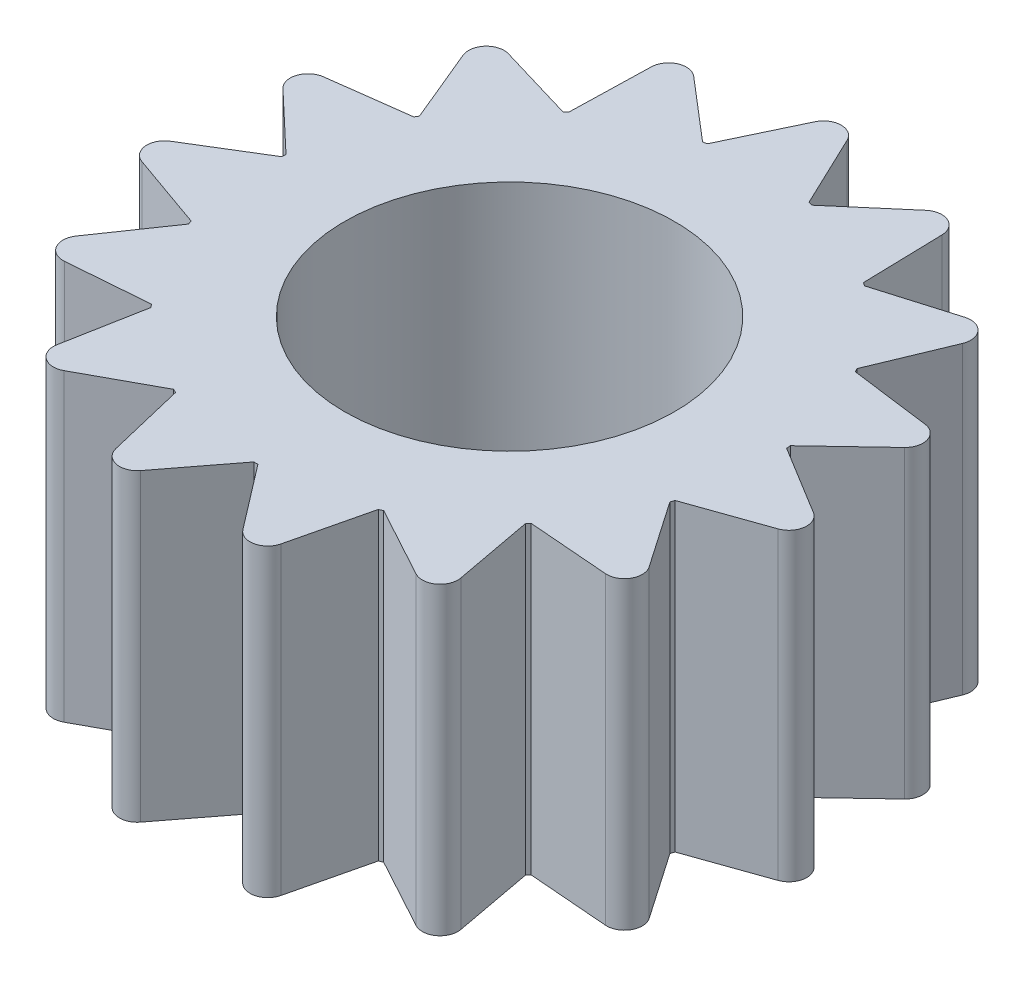
SolidWorks part; units mm, degrees
ref_plane "Front Plane" through (0, 0, 0) normal (0, 0, 1) x (1, 0, 0)
ref_plane "Top Plane" through (0, 0, 0) normal (0, 1, 0) x (1, 0, 0)
ref_plane "Right Plane" through (0, 0, 0) normal (1, 0, 0) x (0, 0, -1)
sketch "Sketch1" plane through (0, 0, 0) normal (0, 1, 0) x (1, 0, 0)
  line L0 (0, 5) -> (0, 7) construction
  line L1 (0, 7) -> (1, 4.899)
  line L2 (0, 7) -> (-1, 4.899)
  line L3 (2.8472, 6.3948) -> (1.079, 4.8822)
  line L4 (2.8472, 6.3948) -> (2.9061, 4.0687)
  line L5 (5.202, 4.6839) -> (2.9715, 4.0212)
  line L6 (5.202, 4.6839) -> (4.3098, 2.5349)
  line L7 (6.6574, 2.1631) -> (4.3502, 2.4649)
  line L8 (6.6574, 2.1631) -> (4.9682, 0.5628)
  line L9 (6.9617, -0.7317) -> (4.9767, 0.4824)
  line L10 (6.9617, -0.7317) -> (4.7676, -1.5066)
  line L11 (6.0622, -3.5) -> (4.7426, -1.5835)
  line L12 (6.0622, -3.5) -> (3.7426, -3.3155)
  line L13 (4.1145, -5.6631) -> (3.6886, -3.3756)
  line L14 (4.1145, -5.6631) -> (2.0705, -4.5511)
  line L15 (1.4554, -6.847) -> (1.9967, -4.584)
  line L16 (1.4554, -6.847) -> (0.0404, -4.9998)
  line L17 (-1.4554, -6.847) -> (-0.0404, -4.9998)
  line L18 (-1.4554, -6.847) -> (-1.9967, -4.584)
  line L19 (-4.1145, -5.6631) -> (-2.0705, -4.5511)
  line L20 (-4.1145, -5.6631) -> (-3.6886, -3.3756)
  line L21 (-6.0622, -3.5) -> (-3.7426, -3.3155)
  line L22 (-6.0622, -3.5) -> (-4.7426, -1.5835)
  line L23 (-6.9617, -0.7317) -> (-4.7676, -1.5066)
  line L24 (-6.9617, -0.7317) -> (-4.9767, 0.4824)
  line L25 (-6.6574, 2.1631) -> (-4.9682, 0.5628)
  line L26 (-6.6574, 2.1631) -> (-4.3502, 2.4649)
  line L27 (-5.202, 4.6839) -> (-4.3098, 2.5349)
  line L28 (-5.202, 4.6839) -> (-2.9715, 4.0212)
  line L29 (-2.8472, 6.3948) -> (-2.9061, 4.0687)
  line L30 (-2.8472, 6.3948) -> (-1.079, 4.8822)
  circle A0 centre (0, 0) radius 3.25
  circle A1 centre (0, 0) radius 5
  point P53 (0, 0)
  point P68 (0, 0)
  dimension "D1" = 6.5
  dimension "D2" = 10
  dimension "D4" = 2
  dimension "D3" = 2
extrude "Boss-Extrude2" add sketch "Sketch1" along normal blind 6
fillet "Fillet1" radius 0.35 15 edges at (0, 3, -7) (2.8472, 3, -6.3948) (5.202, 3, -4.6839) (6.6574, 3, -2.1631) (6.9617, 3, 0.7317) (6.0622, 3, 3.5) (4.1145, 3, 5.6631) (1.4554, 3, 6.847) (-1.4554, 3, 6.847) (-4.1145, 3, 5.6631) (-6.0622, 3, 3.5) (-6.9617, 3, 0.7317) (-2.8472, 3, -6.3948) (-5.202, 3, -4.6839) (-6.6574, 3, -2.1631)
